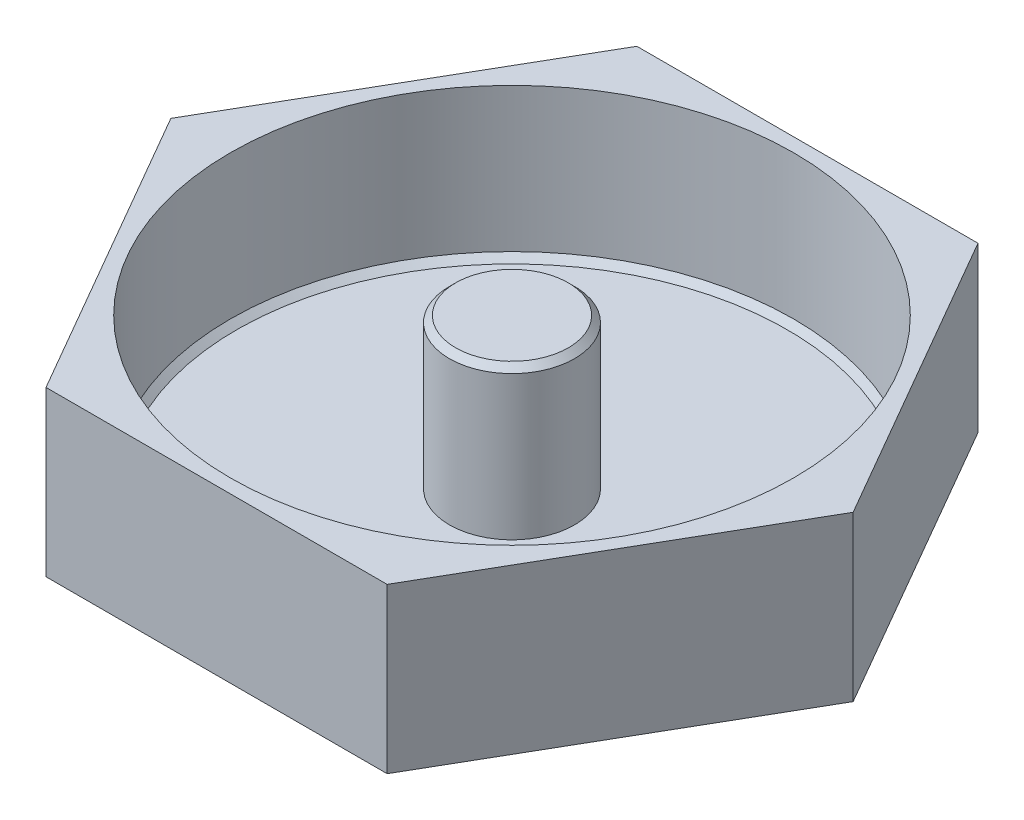
SolidWorks part; units mm, degrees
material "PET"
ref_plane "Front Plane" through (0, 0, 0) normal (0, 0, 1) x (1, 0, 0)
ref_plane "Top Plane" through (0, 0, 0) normal (0, 1, 0) x (1, 0, 0)
ref_plane "Right Plane" through (0, 0, 0) normal (1, 0, 0) x (0, 0, -1)
sketch "Sketch1" plane through (0, 0, 0) normal (0, 1, 0) x (1, 0, 0)
  line L1 (13.6255, 23.6) -> (-13.6255, 23.6)
  line L2 (-13.6255, 23.6) -> (-27.2509, 0)
  line L3 (-27.2509, 0) -> (-13.6255, -23.6)
  line L4 (-13.6255, -23.6) -> (13.6255, -23.6)
  line L5 (13.6255, -23.6) -> (27.2509, 0)
  line L6 (27.2509, 0) -> (13.6255, 23.6)
  circle A0 centre (0, 0) radius 22.5
  circle A1 centre (0, 0) radius 23.6 construction
  circle A2 centre (0, 0) radius 5
  dimension "D2" = 45
  dimension "D4" = 10
  dimension "D1" = 1.1
extrude "Boss-Extrude1" add sketch "Sketch1" along normal blind 12 contours L5 L6 L1 L2 L3 L4 A0 | A2
sketch "Sketch2" plane through (0, 0, 0) normal (0, -1, 0) x (1, 0, 0)
  line L0 (-13.6255, -23.6) -> (-27.2509, 0) construction
  line L1 (13.6255, -23.6) -> (-13.6255, -23.6) construction
  line L2 (27.2509, 0) -> (13.6255, -23.6) construction
  line L3 (13.6255, 23.6) -> (27.2509, 0) construction
  line L4 (-13.6255, 23.6) -> (13.6255, 23.6) construction
  line L5 (-27.2509, 0) -> (-13.6255, 23.6) construction
  line L6 (-13.6255, -23.6) -> (-27.2509, 0)
  line L7 (13.6255, -23.6) -> (-13.6255, -23.6)
  line L8 (27.2509, 0) -> (13.6255, -23.6)
  line L9 (13.6255, 23.6) -> (27.2509, 0)
  line L10 (-13.6255, 23.6) -> (13.6255, 23.6)
  line L11 (-27.2509, 0) -> (-13.6255, 23.6)
extrude "Boss-Extrude2" add sketch "Sketch2" along normal blind 1.1
chamfer "Chamfer1" distance 0.5 angle 45 2 edges at (0, 12, 5) (0, 0, 22.5)
equation "\"tread_diam\" = 45"
equation "\"D2@Sketch1\"=\"tread_diam\""
equation "\"bore_diam\"=10"
equation "\"D4@Sketch1\"=\"bore_diam\""
equation "\"wall_thick\"= 1.1"
equation "\"D1@Sketch1\"=\"wall_thick\""
equation "\"tire_thick\"=12"
equation "\"D1@Boss-Extrude1\"=\"tire_thick\""
equation "\"D1@Boss-Extrude2\"=\"wall_thick\""
